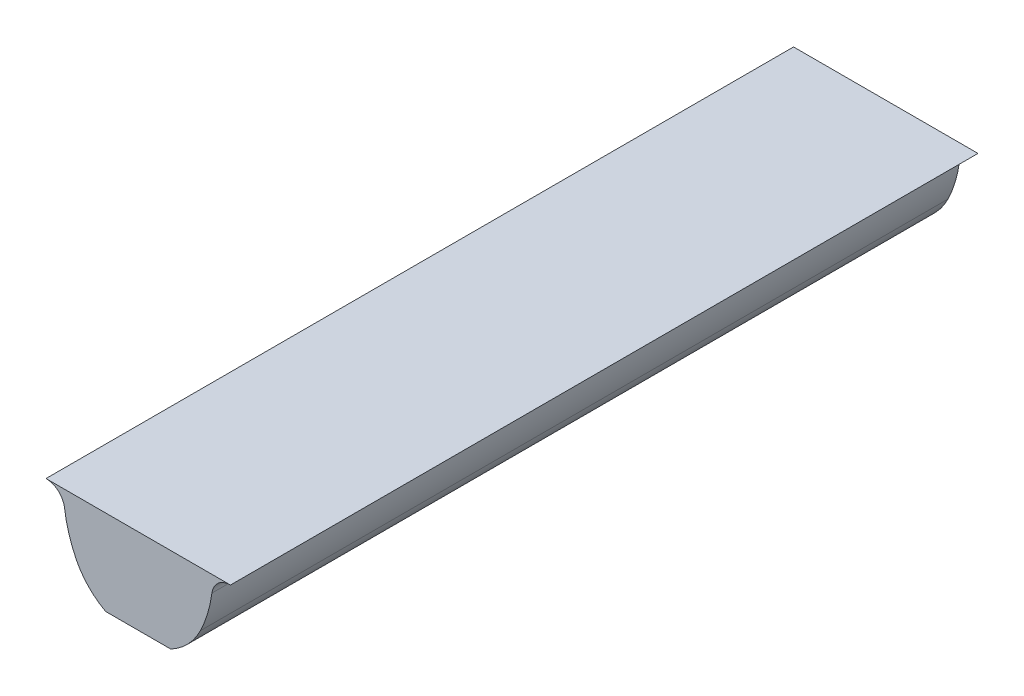
SolidWorks part; units mm, degrees
material "NEOPRENO"
ref_plane "Alzado" through (0, 0, 0) normal (0, 0, 1) x (1, 0, 0)
ref_plane "Planta" through (0, 0, 0) normal (0, 1, 0) x (1, 0, 0)
ref_plane "Vista lateral" through (0, 0, 0) normal (1, 0, 0) x (0, 0, -1)
sketch "Croquis1" plane through (0, 0, 0) normal (0, 0, 1) x (1, 0, 0)
  line L0 (-2.2955, 0) -> (3.15, 0) construction
  line L1 (0.3597, 0.9193) -> (0.3597, -1.0213) construction
  line L2 (-0.3805, 0) -> (1.0999, 0)
  line L3 (0.0987, -0.6848) -> (0.6207, -0.6848)
  arc A1 (-0.2318, -0.1304) -> (-0.1392, -0.4382) centre (0.7597, 0) ccw
  arc A2 (-0.1392, -0.4382) -> (0.0987, -0.6848) centre (0.3597, -0.195) ccw
  arc A3 (-0.2318, -0.1304) -> (-0.3805, 0) centre (-0.3805, -0.15) ccw
  arc A4 (0.9511, -0.1304) -> (1.0999, 0) centre (1.0999, -0.15) cw
  arc A5 (0.9511, -0.1304) -> (0.8586, -0.4382) centre (-0.0403, 0) cw
  arc A6 (0.6207, -0.6848) -> (0.8586, -0.4382) centre (0.3597, -0.195) ccw
  dimension "D1" = 2
  dimension "D3" = 1.11
  dimension "D4" = 0.3
  dimension "D5" = 0.261
  dimension "D2" = 0.4
extrude "Saliente-Extruir1" add sketch "Croquis1" along normal blind 6 contours L2 A4 A5 A6 L3 A2 A1 A3
